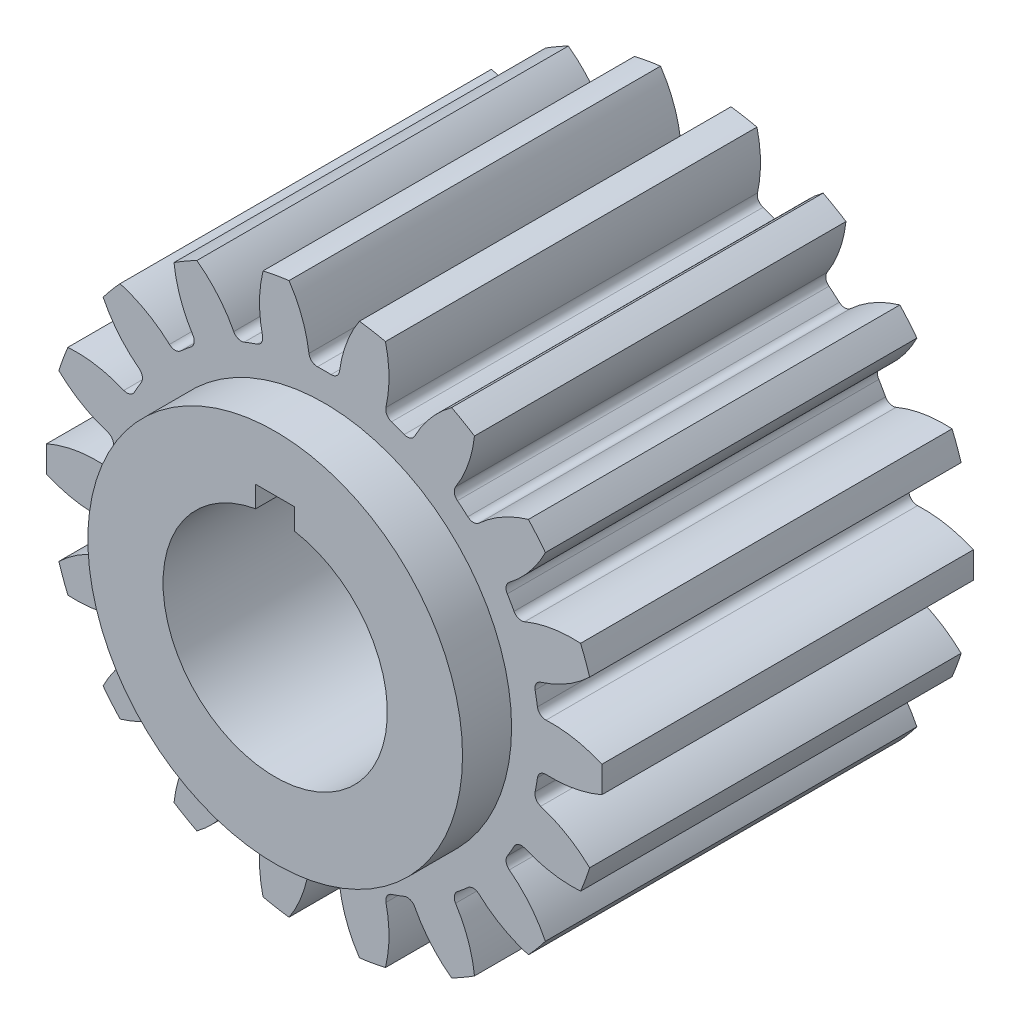
SolidWorks part; units mm, degrees
ref_plane "Front Plane" through (0, 0, 0) normal (0, 0, 1) x (1, 0, 0)
ref_plane "Top Plane" through (0, 0, 0) normal (0, 1, 0) x (1, 0, 0)
ref_plane "Right Plane" through (0, 0, 0) normal (1, 0, 0) x (0, 0, -1)
sketch "Sketch1" plane through (0, 0, 0) normal (0, 0, 1) x (1, 0, 0)
  circle A0 centre (0, 0) radius 17.8416
  circle A1 centre (0, 0) radius 19.824
  circle A2 centre (0, 0) radius 15.3636
  dimension "D1" = 35.6833
  dimension "D3" = 4.4604
  dimension "D2" = 1.9824
extrude "Boss-Extrude1" add sketch "Sketch1" along normal mid plane 26.5 contours A1
sketch "Sketch2" plane through (0, 0, 13.25) normal (0, 0, 1) x (1, 0, 0)
  line L0 (0, 0) -> (0, 19.824) construction
  line L1 (-1.555, 17.7737) -> (1.555, 17.7737) construction
  line L2 (-1.0381, 15.3285) -> (0, 0) construction
  line L3 (0, 13.5014) -> (-2.6056, 20.6604) construction
  line L4 (0, 0) -> (3.4424, 19.5229) construction
  line L5 (1.555, 17.7737) -> (4.6178, 17.2337) construction
  circle A0 centre (0, 0) radius 19.824 construction
  circle A3 centre (0, 0) radius 17.8416 construction
  circle A5 centre (0, 0) radius 19.824 construction
  arc A6 (-3.2066, 20.5757) -> (-1.0381, 15.3285) centre (-9.9271, 14.7265) cw
  arc A7 (3.2066, 20.5757) -> (1.0381, 15.3285) centre (9.9271, 14.7265) ccw
  circle A8 centre (0, 0) radius 15.3636 construction
  arc A10 (1.0381, 15.3285) -> (-1.0381, 15.3285) centre (0, 0) ccw
  circle A13 centre (0, 0) radius 20.824
  arc A14 (3.2066, 20.5757) -> (-3.2066, 20.5757) centre (0, 0) ccw
  dimension "D2" = 20
  dimension "D3" = 10
  dimension "D1" = 1
extrude "Cut-Extrude1" cut sketch "Sketch2" against normal through all
fillet "Fillet1" radius 0.5947 2 edges at (1.0381, 15.3285, 0) (-1.0381, 15.3285, 0)
pattern_circular "CirPattern2" count 18 over 360 about axis through (0, 0, 0) along (0, 0, 1) of "Cut-Extrude1", "Fillet1"
sketch "Sketch3" plane through (0, 0, 13.25) normal (0, 0, 1) x (1, 0, 0)
  line L0 (-1.39, 7.8783) -> (-1.39, 9.39)
  line L1 (-1.39, 9.39) -> (1.39, 9.39)
  line L2 (1.39, 9.39) -> (1.39, 7.8783)
  arc A0 (-1.39, 7.8783) -> (1.39, 7.8783) centre (0, 0) ccw
  point P1 (0, 8)
  dimension "D1" = 16
  dimension "D2" = 2.78
  dimension "D3" = 1.39
extrude "Cut-Extrude2" cut sketch "Sketch3" against normal through all contours A0 L2 L1 L0
sketch "Sketch4" plane through (0, 0, 13.25) normal (0, 0, 1) x (1, 0, 0)
  line L0 (1.39, 9.39) -> (1.39, 7.8783) construction
  line L1 (-1.39, 7.8783) -> (-1.39, 9.39)
  line L2 (1.39, 7.8783) -> (1.39, 9.39)
  line L3 (1.39, 9.39) -> (-1.39, 9.39)
  line L4 (-5.2547, 14.4371) -> (0, 0) construction
  arc A0 (-1.39, 7.8783) -> (1.39, 7.8783) centre (0, 0) ccw
  circle A1 centre (0, 0) radius 13.3636
  arc A4 (-4.7978, 14.5953) -> (-5.7063, 14.2646) centre (0, 0) ccw construction
  point P15 (-4.5706, 12.5577)
  dimension "D1" = 2
extrude "Boss-Extrude3" add sketch "Sketch4" along normal blind 3.5
equation "\"shaft inner diameter\"= 15mm "
equation "\"shaft outer diameter\"= 20mm "
equation "\"column angle\" = 45deg "
equation "\"keyway_height\" = 1.39mm "
equation "\"keyway_width\" = 2.78mm "
equation "\"keyway_length\" = 30mm "
equation "\"steering column length\" = 555mm "
equation "\"steering wheel bolt width\" = 6mm "
equation "\"steering wheel bolt length\" = 40mm "
equation "\"bushing length\" = 40mm "
equation "\"bushing thickness\" = 3mm "
equation "\"u_joint clearance\" = 30mm "
equation "\"u_joint thickness\" = 7.5mm "
equation "\"horizontal shaft length\" = 90mm "
equation "\"short_bearing_outer_width\" = 10mm "
equation "\"column bushing diameter\" = \"primary shaft small diameter\" + 4 "
equation "\"column bushing distance\" = \"steering column length\"/4 "
equation "\"pinion width\" = 26.5mm "
equation "\"pin hole diameter\" = 10mm "
equation "\"rack hole to hole\" = 500mm "
equation "\"rack length\" = \"rack hole to hole\" + \"pin hole diameter\"*2 "
equation "\"rack height\"= \"pin hole diameter\" * 2mm"
equation "\"pitch diameter\" = \"max travel\"/(pi * \"turn to lock\") "
equation "\"D1@Sketch1\"=\"pitch diameter\""
equation "\"D3@Sketch1\"=\"module\" * if( \"module\" => 1.25, 2.25,2.4)"
equation "\"D1@Boss-Extrude1\"=\"pinion width\""
equation "\"pressure angle\" = 20deg "
equation "\"D2@Sketch2\"=\"pressure angle\""
equation "\"D1@Fillet1\"=0.3*\"module\""
equation "\"D1@CirPattern2\" = \"number of teeth\""
equation "\"D3@Sketch2\" = 180deg / \"number of teeth\""
equation "\"D2@Sketch1\"=\"module\""
equation "\"number of teeth\" = 18mm "
equation "\"module\" = \"pitch diameter\" / \"number of teeth\" "
equation "\"D1@Sketch3\"=\"secondary shaft small diameter\""
equation "\"D2@Sketch3\"=\"keyway_width\""
equation "\"D1@Boss-Extrude3\"=\"keyway_length\"-\"pinion width\""
equation "\"D3@Sketch3\"=\"keyway_height\""
equation "\"wheel base\" = 1561mm "
equation "\"track\" = 1354mm "
equation "\"turning radius\" = 2000mm "
equation "\"steering arm length\" = 100mm "
equation "\"turn to lock\" = 0.75mm "
equation "\"max turning angle\" = atn(\"wheel base\" / (\"turning radius\" - 0.5 * \"track\")) "
equation "\"max travel\" = 2 * \"steering arm length\" * sin(0.5 * \"max turning angle\") "
equation "\"primary shaft small diameter\" = 16mm "
equation "\"primary shaft large diameter\" = 24mm "
equation "\"secondary shaft small diameter\" = 16mm "
equation "\"secondary shaft large diameter\" = 25mm "
equation "\"tie rod length\" = 305mm "
equation "\"tie rod inner diameter\" = 6.6mm "
equation "\"tie rod outer diameter\" = 8.1mm "
equation "\"D1@CirPattern1\"=\"pitch diameter\"/(\"module\"*pi)"
